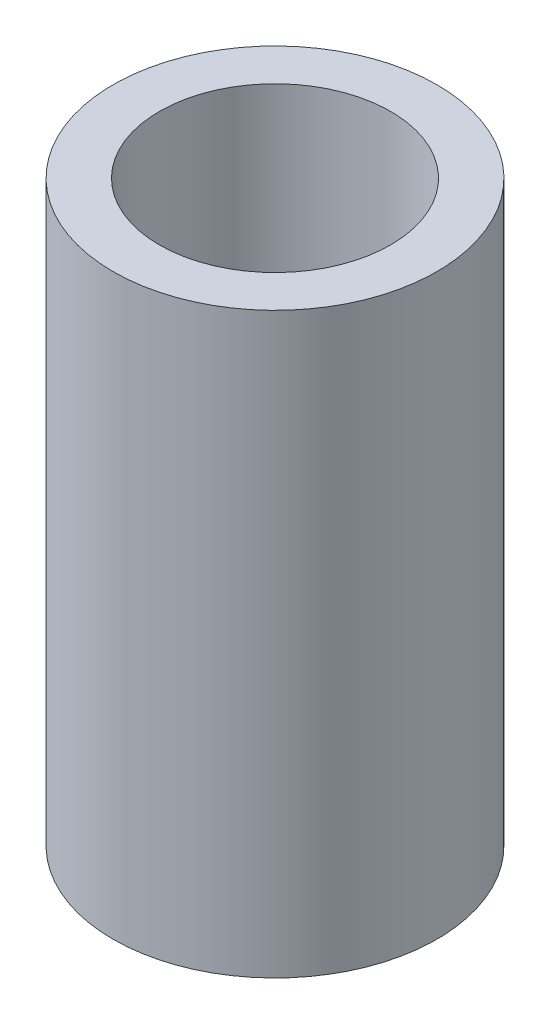
SolidWorks part; units mm, degrees
ref_plane "前视基准面" through (0, 0, 0) normal (0, 0, 1) x (1, 0, 0)
ref_plane "上视基准面" through (0, 0, 0) normal (0, 1, 0) x (1, 0, 0)
ref_plane "右视基准面" through (0, 0, 0) normal (1, 0, 0) x (0, 0, -1)
sketch "草图1" plane through (0, 0, 0) normal (0, 1, 0) x (1, 0, 0)
  circle A0 centre (0, 0) radius 3
  circle A1 centre (0, 0) radius 7
extrude "凸台-拉伸1" add sketch "草图1" along normal blind 12.5
sketch "草图2" plane through (0, 12.5, 0) normal (0, 1, 0) x (1, 0, 0)
  circle A0 centre (0, 0) radius 5
  circle A1 centre (0, 0) radius 7
extrude "凸台-拉伸2" add sketch "草图2" along normal blind 12.5
